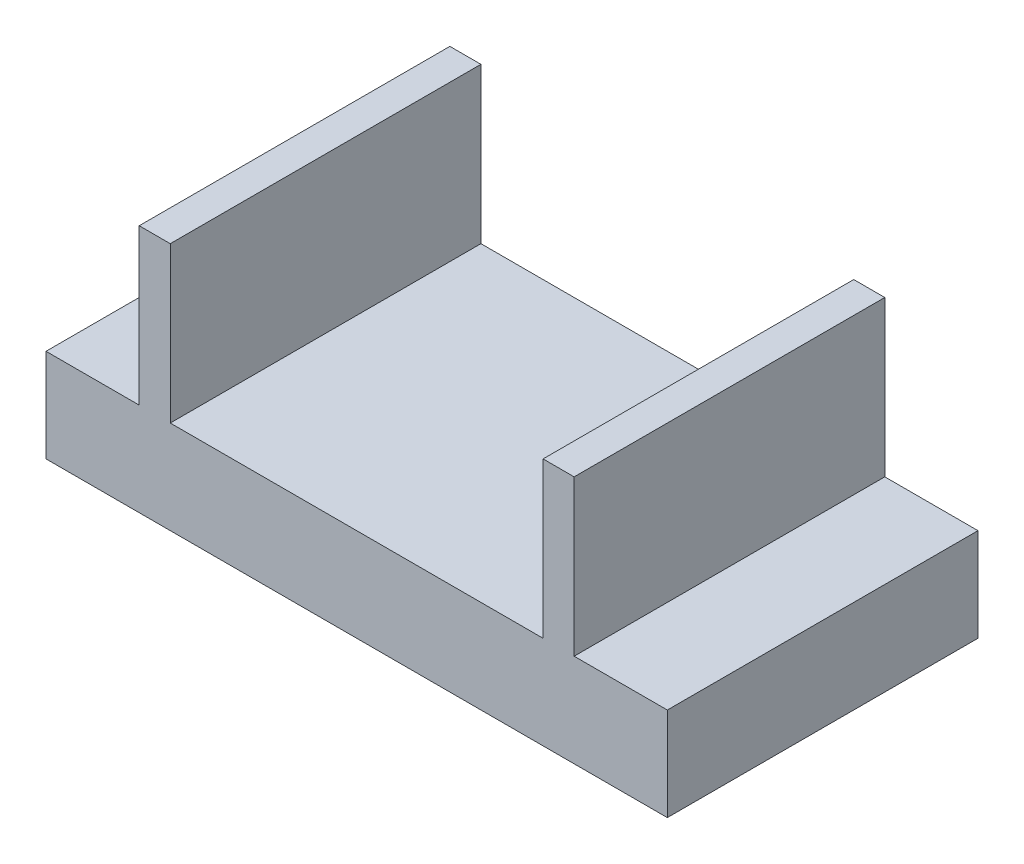
SolidWorks part; units mm, degrees
ref_plane "Спереди" through (0, 0, 0) normal (0, 0, 1) x (1, 0, 0)
ref_plane "Сверху" through (0, 0, 0) normal (0, 1, 0) x (1, 0, 0)
ref_plane "Справа" through (0, 0, 0) normal (1, 0, 0) x (0, 0, -1)
sketch "Эскиз1" plane through (0, 0, 0) normal (0, 0, 1) x (1, 0, 0)
  line L0 (0, 0) -> (20, 0)
  line L1 (0, 0) -> (0, 3)
  line L2 (20, 0) -> (20, 3)
  line L3 (0, 3) -> (3, 3)
  line L4 (20, 3) -> (17, 3)
  line L5 (3, 3) -> (3, 8)
  line L6 (4, 8) -> (3, 8)
  line L7 (4, 8) -> (4, 3)
  line L8 (17, 3) -> (17, 8)
  line L9 (17, 8) -> (16, 8)
  line L10 (16, 8) -> (16, 3)
  line L11 (16, 3) -> (4, 3)
extrude "Бобышка-Вытянуть1" add sketch "Эскиз1" along normal blind 10 contours L0 L2 L4 L8 L9 L10 L11 L7 L6 L5 L3 L1
ref_plane "Плоскость2"
